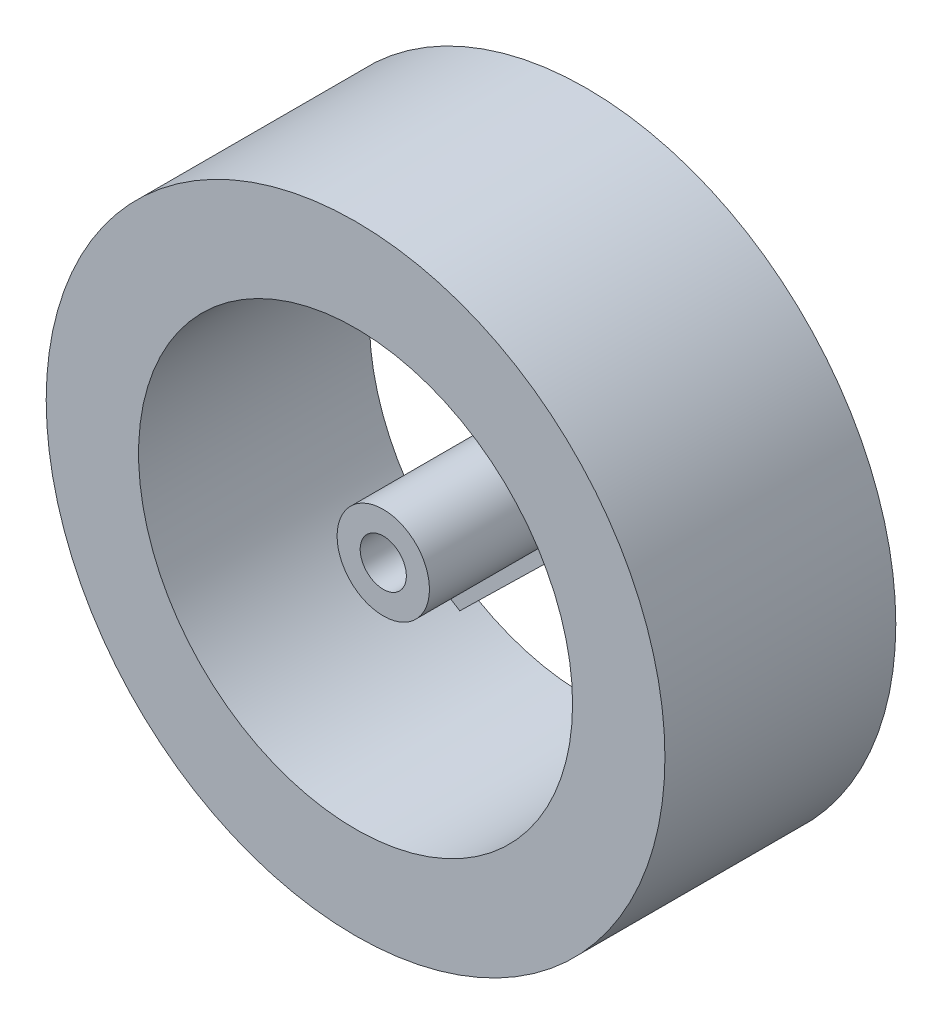
SolidWorks part; units mm, degrees
ref_plane "前基準面" through (0, 0, 0) normal (0, 0, 1) x (1, 0, 0)
ref_plane "上基準面" through (0, 0, 0) normal (0, 1, 0) x (1, 0, 0)
ref_plane "右基準面" through (0, 0, 0) normal (1, 0, 0) x (0, 0, -1)
sketch "草圖1" plane through (0, 0, 0) normal (0, 0, 1) x (1, 0, 0)
  circle A0 centre (0, 0) radius 33.5
  circle A1 centre (0, 0) radius 23.5
  dimension "D1" = 67
  dimension "D2" = 47
extrude "填料-伸長1" add sketch "草圖1" along normal blind 25
sketch "草圖2" plane through (0, 0, 0) normal (0, 0, -1) x (-1, 0, 0)
  line L0 (0, 10) -> (0, 23.5) construction
  line L1 (-5, 8.6603) -> (-2.5, 23.3666)
  line L2 (5, 8.6603) -> (2.5, 23.3666)
  line L3 (6.6913, 7.4314) -> (21.4505, 9.5983)
  line L4 (9.7815, -2.0791) -> (22.9955, 4.843)
  line L5 (9.1355, -4.0674) -> (15.7571, -17.4345)
  line L6 (1.0453, -9.9452) -> (11.712, -20.3735)
  line L7 (-1.0453, -9.9452) -> (-11.712, -20.3735)
  line L8 (-9.1355, -4.0674) -> (-15.7571, -17.4345)
  line L9 (-9.7815, -2.0791) -> (-22.9955, 4.843)
  line L10 (-6.6913, 7.4314) -> (-21.4505, 9.5983)
  circle A0 centre (0, 0) radius 10
  circle A1 centre (0, 0) radius 23.5 construction
  arc A2 (2.5, 23.3666) -> (-2.5, 23.3666) centre (0, 0) ccw
  arc A3 (22.9955, 4.843) -> (21.4505, 9.5983) centre (0, 0) ccw
  arc A4 (11.712, -20.3735) -> (15.7571, -17.4345) centre (0, 0) ccw
  arc A5 (-15.7571, -17.4345) -> (-11.712, -20.3735) centre (0, 0) ccw
  arc A6 (-21.4505, 9.5983) -> (-22.9955, 4.843) centre (0, 0) ccw
  point P29 (0, 0)
  circle M6 centre (0, 0) radius 23.5
  dimension "D1" = 20
  dimension "D2" = 10
  dimension "D3" = 5
  dimension "D4" = 5
extrude "填料-伸長2" add sketch "草圖2" against normal blind 2 contours A0 L0 L1 M6 | L0 A0 L2 A2 | A0 | A0 L10 L9 M6 | A0 L8 L7 M6 | A0 L6 L5 M6 | A0 L4 L3 M6
sketch "草圖3" plane through (0, 0, 2) normal (0, 0, 1) x (1, 0, 0)
  circle A0 centre (0, 0) radius 5
  circle A1 centre (0, 0) radius 2.5
  dimension "D1" = 10
  dimension "D2" = 5
extrude "填料-伸長3" add sketch "草圖3" along normal blind 20
